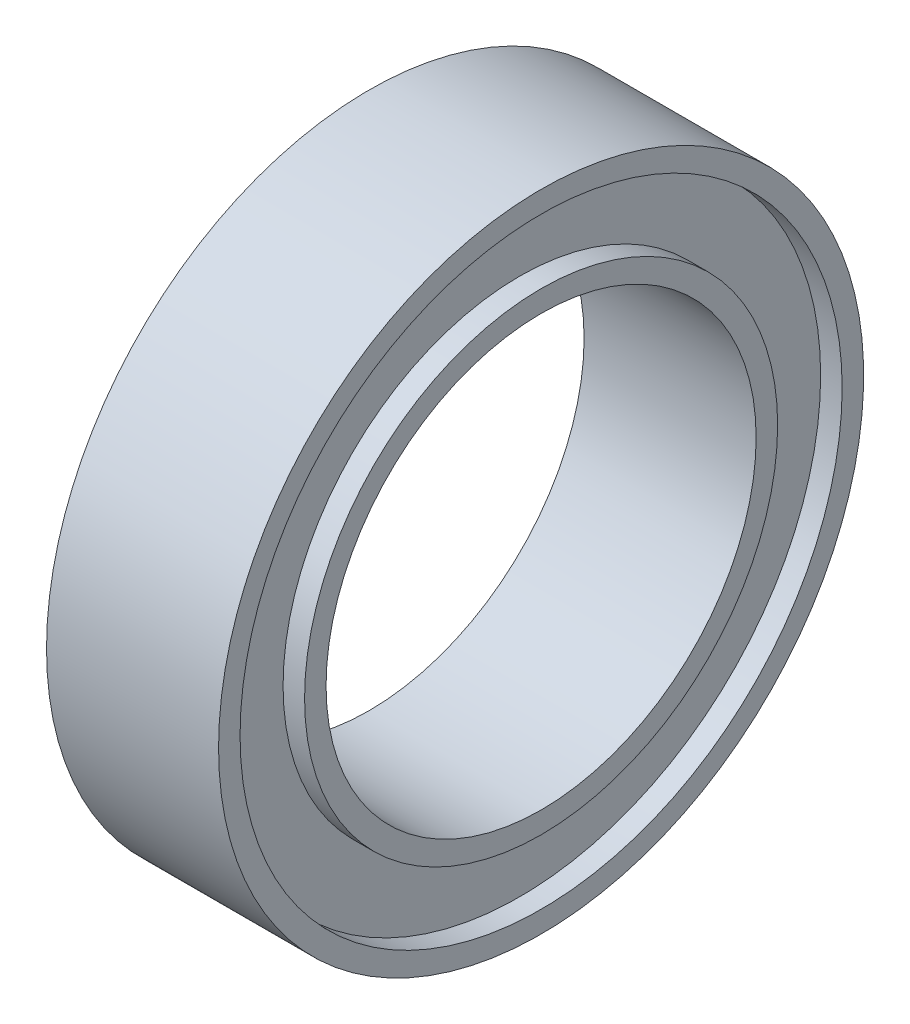
SolidWorks part; units mm, degrees
ref_plane "Plan de face" through (0, 0, 0) normal (0, 0, 1) x (1, 0, 0)
ref_plane "Plan de dessus" through (0, 0, 0) normal (0, 1, 0) x (1, 0, 0)
ref_plane "Plan de droite" through (0, 0, 0) normal (1, 0, 0) x (0, 0, -1)
sketch "Esquisse1" plane through (0, 0, 0) normal (0, 0, 1) x (1, 0, 0)
  line L0 (-31.5428, 0) -> (81.2931, 0) construction
  line L1 (1.5, 5.5) -> (2, 5.5)
  line L2 (-2, 7) -> (-1.5, 7)
  line L3 (-2, 7) -> (-2, 7.5)
  line L4 (-2, 7.5) -> (2, 7.5)
  line L5 (2, 7) -> (2, 7.5)
  line L6 (-2, 7) -> (2, 7.5) construction
  line L7 (-2, 7.5) -> (2, 7) construction
  line L8 (1.5, 7) -> (2, 7)
  line L9 (-1.5, 5.5) -> (-1.5, 7)
  line L11 (1.5, 5.5) -> (1.5, 7)
  line L12 (-1.5, 5.5) -> (1.5, 7) construction
  line L13 (-1.5, 7) -> (1.5, 5.5) construction
  line L14 (-2, 5) -> (2, 5)
  line L15 (-2, 5) -> (-2, 5.5)
  line L16 (-2, 5.5) -> (-1.5, 5.5)
  line L17 (2, 5) -> (2, 5.5)
  line L18 (-2, 5) -> (2, 5.5) construction
  line L19 (-2, 5.5) -> (2, 5) construction
  point P3 (0, 7.25)
  point P8 (0, 6.25)
  point P13 (0, 5.25)
  point P18 (-5.0669, 7.3872)
  dimension "D1" = 7.5
  dimension "D2" = 4
  dimension "D3" = 2
  dimension "D4" = 0.5
  dimension "D6" = 3
  dimension "D7" = 1.5
  dimension "D8" = 5
  dimension "D9" = 5.5
revolve "Révolution1" add sketch "Esquisse1" angle 360 about L0
